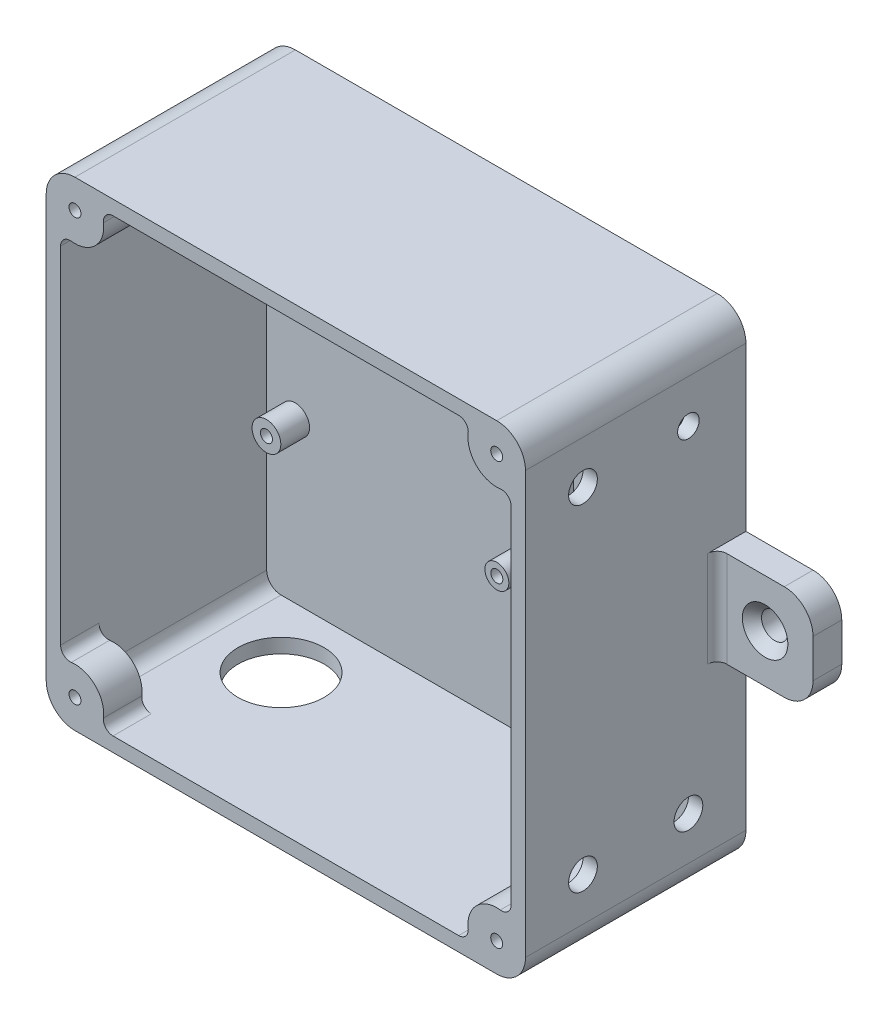
SolidWorks part; units mm, degrees
ref_plane "Front Plane" through (0, 0, 0) normal (0, 0, 1) x (1, 0, 0)
ref_plane "Top Plane" through (0, 0, 0) normal (0, 1, 0) x (1, 0, 0)
ref_plane "Right Plane" through (0, 0, 0) normal (1, 0, 0) x (0, 0, -1)
sketch "Sketch1" plane through (0, 0, 0) normal (0, 0, 1) x (1, 0, 0)
  line L1 (-50, 50) -> (50, 50)
  line L2 (-50, 50) -> (-50, -50)
  line L3 (-50, -50) -> (50, -50)
  line L4 (50, 50) -> (50, -50)
  line L5 (-50, 50) -> (50, -50) construction
  line L6 (-50, -50) -> (50, 50) construction
  point P0 (0, 0)
  dimension "D1" = 100
  dimension "D2" = 100
extrude "Boss-Extrude1" add sketch "Sketch1" along normal blind 46
fillet "Fillet1" radius 6 4 edges at (-50, -50, 23) (50, -50, 23) (50, 50, 23) (-50, 50, 23)
shell "Shell1" thickness 3
sketch "Sketch2" plane through (50, 0, 0) normal (1, 0, 0) x (0, 0, -1)
  line L0 (-46, 50) -> (0, 50) construction
  line L1 (0, -44) -> (0, 44) construction
  line L2 (-46, -44) -> (-46, 44) construction
  line L3 (0, -50) -> (-46, -50) construction
  circle A0 centre (-34, 35) radius 3
  circle A1 centre (-34, -35) radius 3
  circle A2 centre (-12, -35) radius 3
  circle A3 centre (-12, 35) radius 2.25
  dimension "D1" = 6
  dimension "D2" = 6
  dimension "D3" = 6
  dimension "D4" = 4.5
  dimension "D9" = 12
  dimension "D5" = 15
  dimension "D6" = 15
  dimension "D7" = 12
  dimension "D8" = 12
  dimension "D10" = 15
  dimension "D11" = 12
  dimension "D12" = 15
extrude "Cut-Extrude1" cut sketch "Sketch2" against normal blind 10
sketch "Sketch3" plane through (0, 0, 3) normal (0, 0, 1) x (1, 0, 0)
  line L0 (44, 47) -> (-44, 47) construction
  line L1 (37, 27) -> (17, 27)
  line L2 (37, 27) -> (37, -23)
  line L3 (37, -23) -> (17, -23)
  line L4 (17, 27) -> (17, -23)
  line L5 (37, 27) -> (17, -23) construction
  line L6 (37, -23) -> (17, 27) construction
  line L7 (47, -44) -> (47, 44) construction
  line L12 (40, 30) -> (14, 30)
  line L13 (14, 30) -> (14, -26)
  line L14 (40, -26) -> (14, -26)
  line L15 (40, 30) -> (40, -26)
  point P0 (27, 2)
  point P5 (0, 0)
  dimension "D1" = 20
  dimension "D2" = 50
  dimension "D3" = 20
  dimension "D4" = 10
  dimension "D5" = 3
extrude "Boss-Extrude2" add sketch "Sketch3" along normal blind 5
sketch "Sketch4" plane through (0, 0, 3) normal (0, 0, 1) x (1, 0, 0)
  line L0 (-47, 44) -> (-47, -44) construction
  line L1 (44, 47) -> (-44, 47) construction
  line L3 (-44, -47) -> (44, -47) construction
  line L4 (47, -44) -> (47, 44) construction
  line L5 (-44, -47) -> (44, -47) construction
  circle A0 centre (-25.8101, 37) radius 2.5
  circle A1 centre (-25.8101, 37) radius 1.25
  circle A2 centre (-83.6074, -231.1103) radius 2.5
  circle A3 centre (-83.6074, -231.1103) radius 1.25
  circle A4 centre (-83.6074, -231.1103) radius 2.5
  circle A5 centre (-83.6074, -231.1103) radius 1.25
  circle A6 centre (2.1299, 37) radius 1.25
  circle A7 centre (2.1299, 37) radius 2.5
  circle A10 centre (7.03, -15.07) radius 1.25
  circle A11 centre (7.03, -15.07) radius 2.5
  circle A14 centre (-41.0501, -13.8) radius 1.25
  circle A15 centre (-41.0501, -13.8) radius 3
  point P26 (0, 0)
  dimension "D1" = 2.5
  dimension "D2" = 5
  dimension "D7" = 2.5
  dimension "D8" = 5
  dimension "D9" = 31.93
  dimension "D12" = 6
  dimension "D13" = 33.2
  dimension "D11" = 2.5
  dimension "D3" = 21.1899
  dimension "D4" = 10
  dimension "D5" = 2
  dimension "D6" = 27.94
  dimension "D10" = 39.97
  dimension "D14" = 5.9499
extrude "Boss-Extrude3" add sketch "Sketch4" along normal blind 6
sketch "Sketch5" plane through (0, -50, 0) normal (0, -1, 0) x (1, 0, 0)
  line L0 (-44, 0) -> (44, 0) construction
  line L1 (-50, 0) -> (-50, 46) construction
  circle A0 centre (-30, 17) radius 9
  dimension "D1" = 18
  dimension "D2" = 17
  dimension "D3" = 20
extrude "Cut-Extrude2" cut sketch "Sketch5" against normal blind 6
sketch "Sketch6" plane through (0, 0, 46) normal (0, 0, 1) x (1, 0, 0)
  line L0 (44, 44) -> (48.2426, 48.2426) construction
  line L1 (50, -44) -> (50, 44) construction
  arc A0 (50, 44) -> (44, 50) centre (44, 44) ccw construction
  circle A1 centre (44, 44) radius 6
  circle A2 centre (44, 44) radius 1.25
  circle A3 centre (44, -44) radius 6
  circle A4 centre (44, -44) radius 1.25
  circle A5 centre (-44, -44) radius 6
  circle A6 centre (-44, -44) radius 1.25
  circle A7 centre (-44, 44) radius 6
  circle A8 centre (-44, 44) radius 1.25
  point P21 (0, 0)
  dimension "D1" = 12
  dimension "D2" = 2.5
  dimension "D4" = 44
  dimension "D3" = 4
extrude "Boss-Extrude4" add sketch "Sketch6" against normal blind 8
sketch "Sketch7" plane through (0, 0, 0) normal (0, 0, -1) x (-1, 0, 0)
  line L0 (-70, 0) -> (-50, 0) construction
  line L1 (-50, -44) -> (-50, 44) construction
  line L2 (0, 0) -> (0, -22.4744) construction
  line L3 (-50, 10) -> (-64, 10)
  line L4 (-50, 10) -> (-50, -10)
  line L5 (-50, -10) -> (-64, -10)
  line L6 (-70, 4) -> (-70, -4)
  line L7 (-50, 10) -> (-70, -10) construction
  line L8 (-50, -10) -> (-70, 10) construction
  line L9 (50, -10) -> (70, 10) construction
  line L10 (50, 10) -> (70, -10) construction
  line L11 (70, 0) -> (50, 0) construction
  line L12 (70, 4) -> (70, -4)
  line L13 (50, -10) -> (64, -10)
  line L14 (50, 10) -> (50, -10)
  line L15 (50, 10) -> (64, 10)
  circle A0 centre (-60, 0) radius 2.75
  arc A1 (-64, -10) -> (-70, -4) centre (-64, -4) cw
  arc A2 (-64, 10) -> (-70, 4) centre (-64, 4) ccw
  arc A3 (64, 10) -> (70, 4) centre (64, 4) cw
  arc A4 (64, -10) -> (70, -4) centre (64, -4) ccw
  circle A5 centre (60, 0) radius 2.75
  point P4 (-60, 0)
  point P34 (60, 0)
  dimension "D4" = 5.5
  dimension "D5" = 6
  dimension "D1" = 20
  dimension "D2" = 20
  dimension "D3" = 20
extrude "Boss-Extrude5" add sketch "Sketch7" against normal blind 6
chamfer "Chamfer1" distance 2 angle 45 2 edges at (-57.25, 0, 6) (57.25, 0, 6)
fillet "Fillet2" radius 2 10 edges at (50, 0, 6) (-50, 0, 6) (38.8038, -47, 42) (47, -38.8038, 42) (-47, -38.8038, 42) (-38.8038, -47, 42) (-38.8038, 47, 42) (-47, 38.8038, 42) (47, 38.8038, 42) (38.8038, 47, 42)
